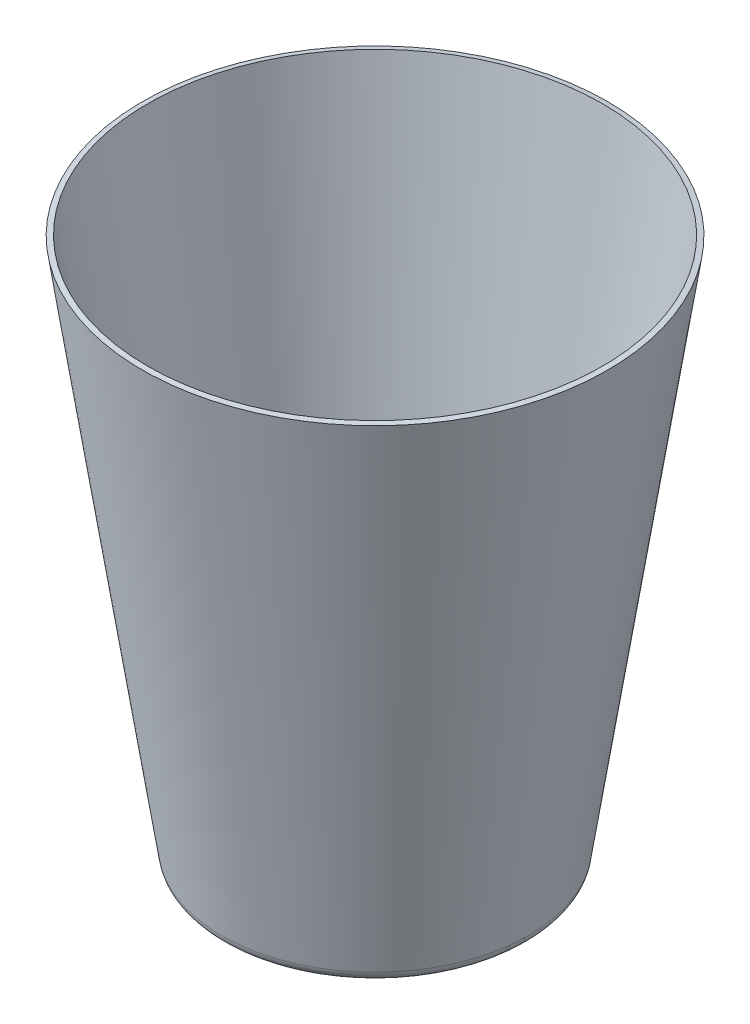
SolidWorks part; units mm, degrees
ref_plane "Front Plane" through (0, 0, 0) normal (0, 0, 1) x (1, 0, 0)
ref_plane "Top Plane" through (0, 0, 0) normal (0, 1, 0) x (1, 0, 0)
ref_plane "Right Plane" through (0, 0, 0) normal (1, 0, 0) x (0, 0, -1)
sketch "Sketch1" plane through (0, 0, 0) normal (0, 0, 1) x (1, 0, 0)
  line L0 (0, 0) -> (0, 128.9453) construction
  line L1 (0, 0) -> (21.4271, 0)
  line L2 (23.4051, 1.7039) -> (35.5, 82.5)
  arc A0 (21.4271, 0) -> (23.4051, 1.7039) centre (21.4271, 2) ccw
  point P7 (23.15, 0)
  dimension "D4" = 2
  dimension "D1" = 46.3
  dimension "D2" = 82.5
  dimension "D3" = 71
revolve "Revolve-Thin1" add sketch "Sketch1" angle 360 about L0 wall 0.8
